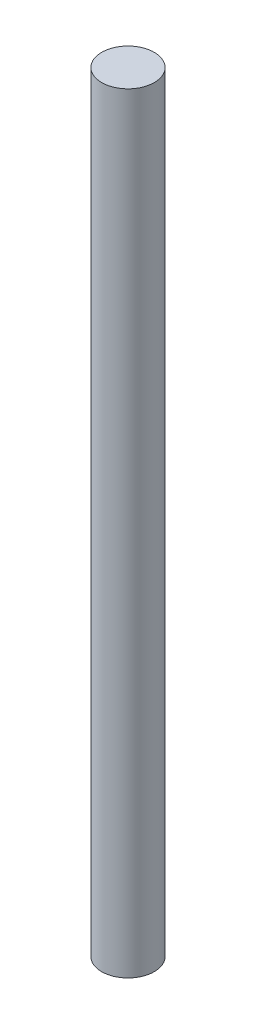
SolidWorks part; units mm, degrees
ref_plane "Front Plane" through (0, 0, 0) normal (0, 0, 1) x (1, 0, 0)
ref_plane "Top Plane" through (0, 0, 0) normal (0, 1, 0) x (1, 0, 0)
ref_plane "Right Plane" through (0, 0, 0) normal (1, 0, 0) x (0, 0, -1)
sketch "Sketch1" plane through (0, 0, 0) normal (0, 1, 0) x (1, 0, 0)
  circle A0 centre (0, 0) radius 0.75
  dimension "D1" = 1.5
extrude "Boss-Extrude1" add sketch "Sketch1" along normal blind 22
